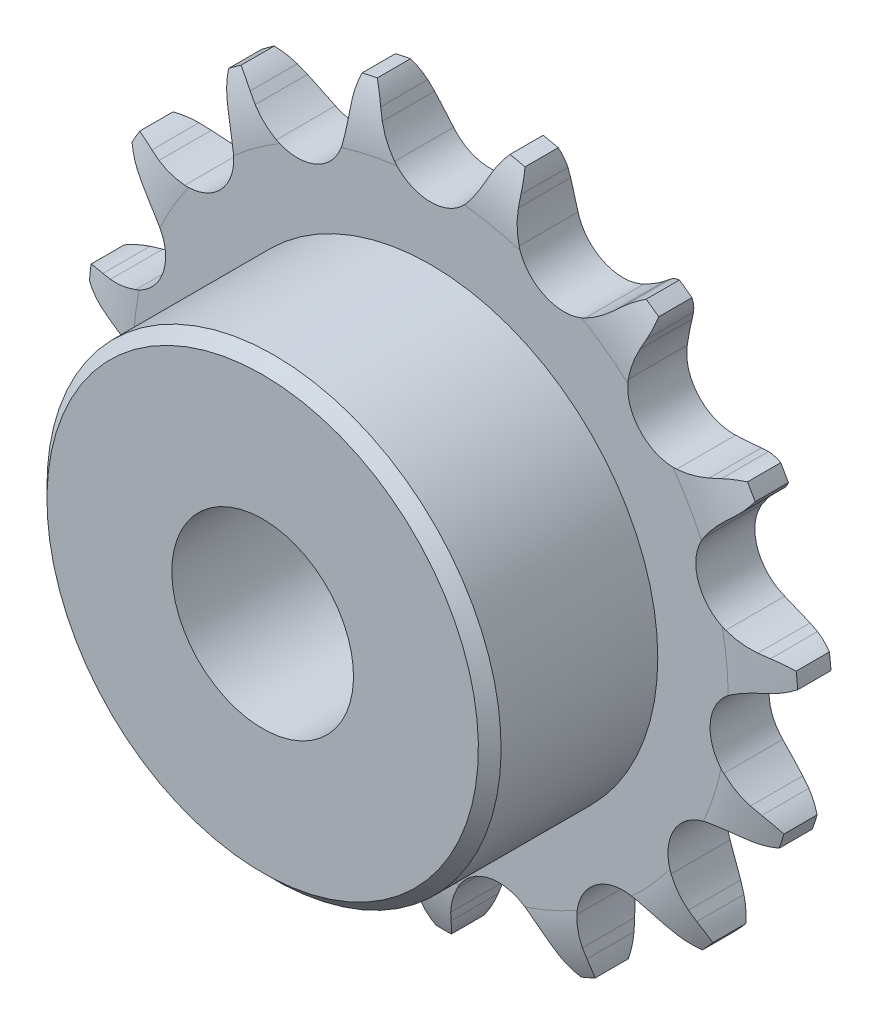
SolidWorks part; units mm, degrees
ref_plane "Front Plane" through (0, 0, 0) normal (0, 0, 1) x (1, 0, 0)
ref_plane "Top Plane" through (0, 0, 0) normal (0, 1, 0) x (1, 0, 0)
ref_plane "Right Plane" through (0, 0, 0) normal (1, 0, 0) x (0, 0, -1)
sketch "Sketch0" plane through (0, 0, 0) normal (0, 0, 1) x (1, 0, 0)
  line L0 (3, -14.1139) -> (0, 0) construction
  line L1 (0, 0) -> (8.4813, -11.6735) construction
  line L2 (0, 0) -> (-3, -14.1139) construction
  line L3 (3, -14.1139) -> (8.4813, -11.6735) construction
  line L4 (3, -14.1139) -> (-3, -14.1139) construction
  line L5 (5.4587, -13.8191) -> (5.1921, -13.4619)
  line L6 (3, -14.1139) -> (0, -14.7516) construction
  line L7 (0.6339, -14.8447) -> (0.7322, -14.4099)
  line L8 (0, -14.1139) -> (0, -15.9139) construction
  line L9 (4.2889, -12.5222) -> (0.9862, -16.6008) construction
  line L10 (0, 0) -> (0, -14.1139) construction
  line L11 (5.1921, -13.4619) -> (0.9862, -16.6008) construction
  line L12 (0, -15.9139) -> (0, -16.1712) construction
  line L13 (8.1159, -11.8362) -> (5.4587, -13.8191) construction
  circle A0 centre (0, 0) radius 15.9139 construction
  circle A1 centre (0, 0) radius 14.4292 construction
  arc A2 (-3.2007, -17.3745) -> (9.9908, -14.5706) centre (0, 0) ccw
  circle A3 centre (0, 0) radius 16.1712 construction
  circle A4 centre (3, -14.1139) radius 2 construction
  arc A7 (4.2889, -12.5222) -> (1.1751, -13.1841) centre (3, -14.1139) ccw
  circle A8 centre (3, -14.1139) radius 2.0481 construction
  arc A9 (5.4587, -13.8191) -> (9.9908, -14.5706) centre (8.1159, -11.8362) ccw
  arc A10 (5.1921, -13.4619) -> (4.2889, -12.5222) centre (0.9862, -16.6008) ccw
  arc A11 (0.6339, -14.8447) -> (-3.2007, -17.3745) centre (-2.6, -14.1139) cw
  arc A12 (0.7322, -14.4099) -> (1.1751, -13.1841) centre (5.8512, -15.5667) cw
  dimension "D1" = 2.0481
  dimension "R" = 2.0481
sketch "Sketch1" plane through (0, 0, 0) normal (1, 0, 0) x (0, 0, -1)
  line L0 (1.3, 0) -> (-1.3, 0)
  line L1 (-1.3, 0) -> (-1.3, 13.1014)
  line L2 (-1.3, 14.4292) -> (0, 14.4292) construction
  line L3 (-0.6, 15.9139) -> (0.6, 15.9139)
  line L5 (1.3, 13.1014) -> (1.3, 0)
  line L7 (0, 15.9139) -> (0, 0) construction
  line L8 (-1.3, 13.1014) -> (1.3, 13.1014) construction
  line L9 (0, 15.9139) -> (0, -15.9139) construction
  line L10 (-1.3, 13.1014) -> (-1.3, 15.9139) construction
  line L11 (-1.3, 15.9139) -> (-0.6, 15.9139) construction
  line L12 (0.6, 15.9139) -> (1.3, 15.9139) construction
  line L13 (1.3, 15.9139) -> (1.3, 13.1014) construction
  line L14 (0, 0) -> (-6.4008, 0) construction
  line L15 (-1.3, 14.4292) -> (-1.3, 10.3292) construction
  line L22 (1.3, 0) -> (-8.7, 0) construction
  line L24 (-1.3, 0) -> (-1.3, 10.3292) construction
  arc A0 (-0.6, 15.9139) -> (-1.3, 13.1014) centre (4.7, 13.1014) ccw
  arc A1 (0.6, 15.9139) -> (1.3, 13.1014) centre (-4.7, 13.1014) cw
  dimension "R" = 6
revolve "Revolve1" add sketch "Sketch1" angle 360 mid plane about L0
extrude "Cut-Extrude1" cut sketch "Sketch0" against normal through all and the other way through all
pattern_circular "CirPattern1" count 15 over 360 about axis through (0, 0, 0) along (0, 0, 1) of "Cut-Extrude1"
sketch "Sketch2" plane through (0, 0, 0) normal (0, 0, 1) x (1, 0, 0)
  circle A0 centre (0, 0) radius 3 construction
  circle A1 centre (0, 0) radius 10
  circle A2 centre (0, 0) radius 15.65 construction
  dimension "Bore" = 6
  dimension "Hub Dia." = 20
  dimension "OD" = 31.3
extrude "Boss-Extrude1" add sketch "Sketch2" along normal up to vertex (8.7 mm away) from surface at 1.3 starting at face at (0, 0, 1.3)
sketch "Sketch3" plane through (0, 0, 0) normal (0, 0, 1) x (1, 0, 0)
  circle A0 centre (0, 0) radius 3 construction
  circle A1 centre (0, 0) radius 3
extrude "Cut-Extrude2" cut sketch "Sketch3" along normal through all and the other way through all
sketch "Sketch4" plane through (0, 0, 0) normal (1, 0, 0) x (0, 0, -1)
  line L0 (-8.7, 10) -> (-8.7, 9.5)
  line L1 (-1.3, 15.9139) -> (-3.25, 15.9139)
  line L2 (-1.3, 15.9139) -> (-1.3, 10.3292)
  line L3 (-1.3, 10.3292) -> (-3.25, 10.3292)
  line L4 (-3.25, 15.9139) -> (-3.25, 10.3292)
  line L9 (-8.7, 9.5) -> (-8.2, 10)
  line L10 (-8.2, 10) -> (-8.7, 10)
  dimension "C" = 0.5
  dimension "D3" = 1.95
revolve "Cut-Revolve1" cut sketch "Sketch4" angle 360 mid plane about L22
sketch "Sketch5" plane through (0, 0, 0) normal (0, 0, 1) x (1, 0, 0)
  circle A0 centre (0, 0) radius 15.65 construction
  circle A1 centre (0, 0) radius 15.65
extrude "Cut-Extrude3" cut sketch "Sketch5" against normal through all and the other way through all flip side to cut
sketch "Sketch6" plane through (0, 0, -1.3) normal (0, 0, -1) x (-1, 0, 0)
  circle A0 centre (0, 0) radius 4
  dimension "D1" = 8
extrude "Cut-Extrude4" cut sketch "Sketch6" against normal through all
equation "\"360/N@Sketch0\" = 360/\"Teeth@CirPattern1\""
equation "\"Ds@Sketch0\" = 1.005 * \"Dr@Sketch0\" + ( 0.003 * 25.4 ) "
equation "\"R@Sketch0\" = 1/2 * \"Ds@Sketch0\""
equation "\"A@Sketch0\" = 35 +  ( 60 / \"Teeth@CirPattern1\" ) "
equation "\"B@Sketch0\" = 18 -  ( 56 / \"Teeth@CirPattern1\" )"
equation "\"ac@Sketch0\" = 0.8 * \"Dr@Sketch0\""
equation "\"ab@Sketch0\" = 1.4 * \"Dr@Sketch0\""
equation "\"J@Sketch0\" = 0.3 * \"Pitch@Sketch0\""
equation "\"D3@Sketch4\" = \"t@Sketch1\" * 3 / 4"
